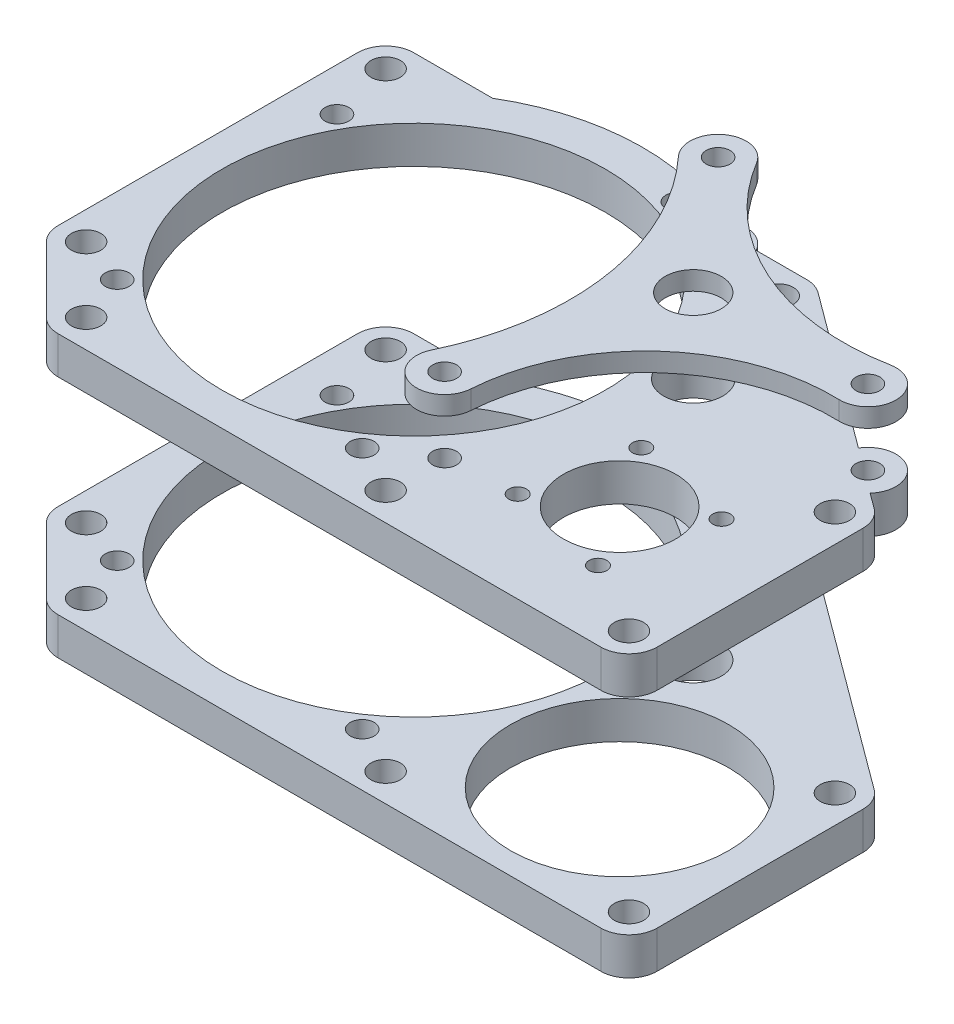
SolidWorks part; units mm, degrees
other "Outer Bottom Plate"
other "Outer Top Plate"
other "Stage 2 Retaining Plate"
material "Alum Plate"
ref_plane "Front Plane" through (0, 0, 0) normal (0, 0, 1) x (1, 0, 0)
ref_plane "Top Plane" through (0, 0, 0) normal (0, 1, 0) x (1, 0, 0)
ref_plane "Right Plane" through (0, 0, 0) normal (1, 0, 0) x (0, 0, -1)
other "Bounding Box"
ref_plane "Default Plane" through (-8.9266, -12.7485, 0) normal (-0.1736, 0.9848, 0) x (0.9848, 0.1736, 0)
sketch "Sketch1" plane through (0, 0, 0) normal (0, 1, 0) x (1, 0, 0)
  line L0 (-38.1, 76.2) -> (-38.1, -38.1)
  line L1 (-38.1, -38.1) -> (76.2, -38.1)
  line L2 (-38.1, 0) -> (0, 0) construction
  line L3 (0, 0) -> (0, -38.1) construction
  line L4 (-29.9699, -25.5926) -> (-25.5926, -29.9699) construction
  line L5 (-38.1, -38.1) -> (-27.7812, -27.7812) construction
  line L6 (-33.3375, -22.225) -> (-33.3375, 0) construction
  line L7 (-33.3375, 0) -> (-33.3375, 28.575) construction
  line L8 (-22.225, -33.3375) -> (0, -33.3375) construction
  line L9 (0, -33.3375) -> (28.575, -33.3375) construction
  line L10 (28.575, -33.3375) -> (69.85, -33.3375) construction
  circle A0 centre (0, 0) radius 32.5
  circle A1 centre (0, 0) radius 25
  circle A3 centre (50.8, -15.875) radius 17.5006
  circle A4 centre (0, 0) radius 31.115
  circle A5 centre (50.8, -15.875) radius 6.35
  circle A6 centre (38.3007, 9.1132) radius 8.255
  circle A7 centre (38.3007, 9.1132) radius 21.59
  circle A8 centre (-22.225, -33.3375) radius 4.7625
  circle A9 centre (-33.3375, 28.575) radius 4.7625
  circle A10 centre (69.85, -33.3375) radius 4.7625
  circle A11 centre (-33.3375, -22.225) radius 4.7625
  circle A12 centre (28.575, -33.3375) radius 4.7625
  point P24 (32.5, 0)
  point P26 (-32.5, 0)
  point P27 (33.2994, -15.875)
  point P38 (68.3006, -15.875)
  dimension "D1" = 65
  dimension "D2" = 50
  dimension "D3" = 35.0012
  dimension "D4" = 62.23
  dimension "D5" = 12.7
  dimension "D6" = 16.51
  dimension "D8" = 9.525
  dimension "D9" = 43.18
  dimension "D7" = 38.1
  dimension "D10" = 114.3
  dimension "D11" = 88.9
  dimension "D12" = 15.875
  dimension "D13" = 22.225
  dimension "D14" = 107.95
  dimension "D15" = 66.675
sketch "Sketch2" plane through (0, 0, 0) normal (0, 0, 1) x (1, 0, 0)
  line L0 (0, 0) -> (0, 19.05) construction
  line L1 (0, 19.05) -> (0, 24.1) construction
  line L2 (-32.5, 31.1) -> (32.5, 31.1)
  line L3 (-32.5, 31.1) -> (-32.5, 24.1)
  line L4 (-32.5, 24.1) -> (32.5, 24.1)
  line L5 (32.5, 31.1) -> (32.5, 24.1)
  line L6 (-32.5, 31.1) -> (32.5, 24.1) construction
  line L7 (-32.5, 24.1) -> (32.5, 31.1) construction
  line L8 (-32.5, 73.025) -> (32.5, 73.025)
  line L9 (-32.5, 73.025) -> (-32.5, 66.025)
  line L10 (-32.5, 66.025) -> (32.5, 66.025)
  line L11 (32.5, 73.025) -> (32.5, 66.025)
  line L12 (-32.5, 73.025) -> (32.5, 66.025) construction
  line L13 (-32.5, 66.025) -> (32.5, 73.025) construction
  line L14 (0, 31.1) -> (0, 66.025) construction
  line L15 (33.2994, 31.4297) -> (38.989, 21.575)
  line L16 (-38.1, 24.75) -> (83.6339, 24.75)
  line L17 (-38.1, 24.75) -> (-38.1, 31.1)
  line L18 (-38.1, 31.1) -> (83.6339, 31.1)
  line L19 (83.6339, 24.75) -> (83.6339, 31.1)
  line L20 (-38.1, 72.375) -> (83.6339, 72.375)
  line L21 (-38.1, 72.375) -> (-38.1, 66.025)
  line L22 (-38.1, 66.025) -> (83.6339, 66.025)
  line L23 (83.6339, 72.375) -> (83.6339, 66.025)
  line L24 (38.989, 21.575) -> (62.611, 21.575)
  line L25 (33.2994, 31.4297) -> (33.2994, 66.025)
  line L26 (33.2994, 66.025) -> (68.3006, 66.025)
  line L27 (68.3006, 31.4297) -> (68.3006, 66.025)
  line L28 (36.5821, 25.7439) -> (68.3006, 66.025) construction
  line L29 (33.2994, 66.025) -> (65.0179, 25.7439) construction
  line L30 (68.3006, 31.4297) -> (62.611, 21.575)
  line L31 (33.2994, 21.575) -> (33.2994, 31.4297) construction
  line L32 (33.2994, 21.575) -> (36.5821, 25.7439) construction
  line L33 (33.2994, 21.575) -> (38.989, 21.575) construction
  line L34 (62.611, 21.575) -> (68.3006, 21.575) construction
  line L35 (65.0179, 25.7439) -> (68.3006, 21.575) construction
  line L36 (68.3006, 21.575) -> (68.3006, 31.4297) construction
  line L37 (50.8, 21.575) -> (50.8, 66.025) construction
  line L38 (0, 0) -> (-69.131, 0) construction
  line L39 (-61.9887, 88.9) -> (127.3908, 88.9) construction
  line L41 (0, 85.075) -> (50.8, 85.075)
  line L42 (0, 85.075) -> (0, 81.9)
  line L43 (0, 81.9) -> (50.8, 81.9)
  line L44 (50.8, 85.075) -> (50.8, 81.9)
  line L45 (0, 85.075) -> (50.8, 81.9) construction
  line L46 (0, 81.9) -> (50.8, 85.075) construction
  circle A0 centre (0, 19.05) radius 19.05
  point P3 (0, 27.6)
  point P9 (0, 69.525)
  point P32 (50.8, 43.8)
  point P43 (25.4, 83.4875)
  dimension "D1" = 38.1
  dimension "D2" = 7
  dimension "D3" = 34.925
  dimension "D4" = 73.025
  dimension "D5" = 88.9
  dimension "D6" = 6.35
  dimension "D7" = 30
  dimension "D8" = 44.45
  dimension "D9" = 23.622
  dimension "D10" = 9.525
  dimension "D11" = 3.175
ref_plane "Plane1" through (0, 31.1, 0) normal (0, 1, 0) x (1, 0, 0)
sketch "Sketch3" plane through (0, 31.1, 0) normal (0, 1, 0) x (1, 0, 0)
  line L0 (-38.1, 76.2) -> (-38.1, -38.1) construction
  line L1 (-38.1, -38.1) -> (76.2, -38.1) construction
  line L2 (-38.1, 28.575) -> (-38.1, -22.225)
  line L3 (-22.225, -38.1) -> (69.85, -38.1)
  line L4 (-36.7051, -25.5926) -> (-25.5926, -36.7051)
  line L5 (-33.3375, 28.575) -> (33.3375, 28.575) construction
  line L6 (69.85, -33.3375) -> (69.85, 1.5875) construction
  line L7 (0, 0) -> (0, 28.575) construction
  line L8 (50.8, -15.875) -> (69.85, -15.875) construction
  line L9 (-33.3375, 33.3375) -> (-19.9483, 33.3375)
  line L10 (36.1683, 32.4049) -> (72.6808, 5.4174)
  line L11 (74.6125, 1.5875) -> (74.6125, -33.3375)
  line L12 (19.9483, 33.3375) -> (33.3375, 33.3375)
  circle A0 centre (0, 0) radius 32.5 construction
  circle A1 centre (0, 0) radius 32.5
  circle A2 centre (-33.3375, -22.225) radius 4.7625 construction
  circle A3 centre (-22.225, -33.3375) radius 4.7625 construction
  arc A4 (-38.1, -22.225) -> (-36.7051, -25.5926) centre (-33.3375, -22.225) ccw
  arc A5 (-25.5926, -36.7051) -> (-22.225, -38.1) centre (-22.225, -33.3375) ccw
  circle A6 centre (-33.3375, 28.575) radius 2.4892
  circle A7 centre (-33.3375, -22.225) radius 2.4892
  circle A8 centre (-22.225, -33.3375) radius 2.4892
  circle A9 centre (28.575, -33.3375) radius 2.4892
  circle A10 centre (50.8, -15.875) radius 18.5166
  circle A11 centre (38.3007, 9.1132) radius 4.7625
  circle A12 centre (50.8, -15.875) radius 17.5006 construction
  circle A13 centre (69.85, -33.3375) radius 2.4892
  circle A14 centre (69.85, 1.5875) radius 2.4892
  circle A15 centre (33.3375, 28.575) radius 2.4892
  arc A16 (33.3375, 33.3375) -> (36.1683, 32.4049) centre (33.3375, 28.575) cw
  arc A17 (74.6125, 1.5875) -> (72.6808, 5.4174) centre (69.85, 1.5875) ccw
  arc A18 (-38.1, 28.575) -> (-33.3375, 33.3375) centre (-33.3375, 28.575) cw
  circle A19 centre (-33.3375, 28.575) radius 4.7625 construction
  arc A20 (69.85, -38.1) -> (74.6125, -33.3375) centre (69.85, -33.3375) ccw
  circle A21 centre (69.85, -33.3375) radius 4.7625 construction
  arc A22 (-19.9483, 33.3375) -> (19.9483, 33.3375) centre (0, 0) cw
  dimension "D1" = 4.9784
  dimension "D2" = 1.016
  dimension "D3" = 9.525
  dimension "D4" = 6.35
extrude "Boss-Extrude1" add sketch "Sketch3" against normal up to vertex (6.35 mm away) up to point (-38.1, 24.75, 0)
ref_plane "Plane2" through (0, 66.025, 0) normal (0, 1, 0) x (1, 0, 0)
sketch "Sketch4" plane through (0, 66.025, 0) normal (0, 1, 0) x (1, 0, 0)
  line L0 (24.7301, 25.9051) -> (23.5327, 27.3867) construction
  line L1 (61.7669, 10.2769) -> (59.8642, 10.1825) construction
  line L2 (62.4497, 12.9795) -> (36.1683, 32.4049)
  line L7 (-36.7051, -25.5926) -> (-25.5926, -36.7051)
  line L8 (-22.225, -38.1) -> (69.85, -38.1)
  line L9 (74.6125, -33.3375) -> (74.6125, 1.5875)
  line L10 (72.6808, 5.4174) -> (36.1683, 32.4049)
  line L11 (33.3375, 33.3375) -> (19.9483, 33.3375)
  line L12 (-19.9483, 33.3375) -> (-33.3375, 33.3375)
  line L13 (-38.1, 28.575) -> (-38.1, -22.225)
  line L14 (-36.7051, -25.5926) -> (-25.5926, -36.7051)
  line L15 (-22.225, -38.1) -> (69.85, -38.1)
  line L16 (74.6125, -33.3375) -> (74.6125, 1.5875)
  line L17 (72.6808, 5.4174) -> (70.077, 7.3419)
  line L18 (33.3375, 33.3375) -> (24.7384, 33.3375)
  line L19 (-19.9483, 33.3375) -> (-33.3375, 33.3375)
  line L20 (-38.1, 28.575) -> (-38.1, -22.225)
  circle A0 centre (33.3375, 28.575) radius 2.4892 construction
  circle A1 centre (69.85, 1.5875) radius 2.4892 construction
  circle A2 centre (69.85, -33.3375) radius 2.4892 construction
  circle A3 centre (28.575, -33.3375) radius 2.4892 construction
  circle A4 centre (-22.225, -33.3375) radius 2.4892 construction
  circle A5 centre (-33.3375, -22.225) radius 2.4892 construction
  circle A6 centre (-33.3375, 28.575) radius 2.4892 construction
  arc A7 (-38.1, -22.225) -> (-36.7051, -25.5926) centre (-33.3375, -22.225) ccw
  arc A8 (-25.5926, -36.7051) -> (-22.225, -38.1) centre (-22.225, -33.3375) ccw
  arc A9 (69.85, -38.1) -> (74.6125, -33.3375) centre (69.85, -33.3375) ccw
  arc A10 (74.6125, 1.5875) -> (72.6808, 5.4174) centre (69.85, 1.5875) ccw
  arc A11 (36.1683, 32.4049) -> (33.3375, 33.3375) centre (33.3375, 28.575) ccw
  arc A12 (19.9483, 33.3375) -> (-19.9483, 33.3375) centre (0, 0) ccw
  arc A13 (-33.3375, 33.3375) -> (-38.1, 28.575) centre (-33.3375, 28.575) ccw
  arc A14 (-38.1, -22.225) -> (-36.7051, -25.5926) centre (-33.3375, -22.225) ccw
  arc A15 (-25.5926, -36.7051) -> (-22.225, -38.1) centre (-22.225, -33.3375) ccw
  arc A16 (69.85, -38.1) -> (74.6125, -33.3375) centre (69.85, -33.3375) ccw
  arc A17 (74.6125, 1.5875) -> (72.6808, 5.4174) centre (69.85, 1.5875) ccw
  arc A18 (36.1683, 32.4049) -> (33.3375, 33.3375) centre (33.3375, 28.575) ccw
  arc A19 (17.4463, 34.7124) -> (-19.9483, 33.3375) centre (0, 0) ccw
  arc A20 (-33.3375, 33.3375) -> (-38.1, 28.575) centre (-33.3375, 28.575) ccw
  circle A21 centre (33.3375, 28.575) radius 2.4892
  circle A22 centre (69.85, 1.5875) radius 2.4892
  circle A23 centre (69.85, -33.3375) radius 2.4892
  circle A24 centre (28.575, -33.3375) radius 2.4892
  circle A25 centre (-22.225, -33.3375) radius 2.4892
  circle A26 centre (-33.3375, -22.225) radius 2.4892
  circle A27 centre (-33.3375, 28.575) radius 2.4892
  circle A28 centre (38.3007, 9.1132) radius 5.0165
  circle A29 centre (38.3007, 9.1132) radius 4.7625 construction
  circle A30 centre (50.8, -15.875) radius 9.525
  circle A31 centre (0, 0) radius 32.5 construction
  circle A32 centre (0, 0) radius 32.5
  circle A33 centre (20.5392, 31.0908) radius 2.0193
  arc A34 (24.7384, 33.3375) -> (17.4463, 34.7124) centre (20.5392, 31.0908) ccw
  circle A36 centre (66.5236, 10.5128) radius 2.0193
  arc A37 (70.077, 7.3419) -> (62.4497, 12.9795) centre (66.5236, 10.5128) ccw
  circle A38 centre (28.8389, -23.5968) radius 2.0193
  circle A39 centre (28.8389, -23.5968) radius 4.7625 construction
  circle A40 centre (50.8, -15.875) radius 18.5166 construction
  circle A41 centre (38.3007, 9.1132) radius 21.59 construction
  circle A42 centre (69.85, 1.5875) radius 4.7625 construction
  arc A43 (61.7669, 10.2769) -> (68.1868, 6.0501) centre (66.5236, 10.5128) ccw construction
  arc A44 (62.4497, 12.9795) -> (61.7669, 10.2769) centre (66.5236, 10.5128) ccw construction
  arc A45 (23.5327, 27.3867) -> (24.7384, 33.3375) centre (20.5392, 31.0908) ccw construction
  arc A46 (17.4463, 34.7124) -> (17.9141, 27.1171) centre (20.5392, 31.0908) ccw construction
  arc A47 (17.9141, 27.1171) -> (23.5327, 27.3867) centre (20.5392, 31.0908) ccw construction
  circle A48 centre (-33.3375, 28.575) radius 4.7625 construction
  arc A49 (68.1868, 6.0501) -> (70.077, 7.3419) centre (66.5236, 10.5128) ccw construction
  dimension "D2" = 0.254
  dimension "D3" = 19.05
  dimension "D5" = 4.0386
  dimension "D4" = 1.905
  dimension "D1" = 0
extrude "Boss-Extrude2" add sketch "Sketch4" along normal up to vertex (6.35 mm away) separate body up to point (-38.1, 72.375, 0)
ref_plane "Plane3" through (0, 81.9, 0) normal (0, 1, 0) x (1, 0, 0)
sketch "Sketch6" plane through (0, 81.9, 0) normal (0, 1, 0) x (1, 0, 0)
  circle A0 centre (38.3007, 9.1132) radius 4.7625 construction
  circle A1 centre (28.8389, -23.5968) radius 2.0193 construction
  circle A2 centre (66.5236, 10.5128) radius 2.0193 construction
  circle A3 centre (20.5392, 31.0908) radius 2.0193 construction
  circle A4 centre (38.3007, 9.1132) radius 4.7625
  circle A5 centre (28.8389, -23.5968) radius 2.0193
  circle A6 centre (66.5236, 10.5128) radius 2.0193
  circle A7 centre (20.5392, 31.0908) radius 2.0193
  arc A8 (24.6177, 33.5499) -> (17.0461, 27.8535) centre (20.5392, 31.0908) ccw
  arc A9 (65.6397, 15.1925) -> (66.3605, 5.7531) centre (66.5236, 10.5128) cw
  arc A10 (24.5426, -21.5418) -> (33.5913, -23.9075) centre (28.8389, -23.5968) ccw
  arc A11 (24.6177, 33.5499) -> (65.6397, 15.1925) centre (58.3332, 53.8786) ccw
  arc A12 (33.5913, -23.9075) -> (66.3605, 5.7531) centre (65.2737, -25.9783) cw
  arc A13 (24.5426, -21.5418) -> (17.0461, 27.8535) centre (-15.556, -2.3609) ccw
  circle A16 centre (28.575, -33.3375) radius 4.7625 construction
  arc A17 (24.7384, 33.3375) -> (17.4463, 34.7124) centre (20.5392, 31.0908) ccw construction
  arc A18 (70.077, 7.3419) -> (62.4497, 12.9795) centre (66.5236, 10.5128) ccw construction
  dimension "D1" = 39.37
  dimension "D2" = 31.75
  dimension "D3" = 44.45
extrude "Boss-Extrude3" add sketch "Sketch6" along normal up to vertex (3.175 mm away) separate body up to point (50.8, 85.075, 0)
sketch "Sketch8" plane through (0, 72.375, 0) normal (0, 1, 0) x (1, 0, 0)
  line L0 (40.3166, -22.683) -> (43.992, -5.3916) construction
  line L1 (40.3166, -22.683) -> (57.608, -26.3584) construction
  line L2 (43.992, -5.3916) -> (61.2834, -9.067) construction
  line L3 (57.608, -26.3584) -> (61.2834, -9.067) construction
  line L4 (40.3166, -22.683) -> (61.2834, -9.067) construction
  line L5 (43.992, -5.3916) -> (57.608, -26.3584) construction
  line L6 (50.8, -15.875) -> (52.6377, -7.2293) construction
  line L7 (50.8, -15.875) -> (50.8, -6.35) construction
  circle A0 centre (50.8, -15.875) radius 9.525 construction
  circle A1 centre (43.992, -5.3916) radius 1.5
  circle A2 centre (61.2834, -9.067) radius 1.5
  circle A3 centre (57.608, -26.3584) radius 1.5
  circle A4 centre (40.3166, -22.683) radius 1.5
  point P1 (50.8, -15.875)
  dimension "D2" = 3
  dimension "D1" = 25
  dimension "D3" = 12
extrude "Cut-Extrude1" cut sketch "Sketch8" against normal through all
sketch "Sketch9" plane through (0, 72.375, 0) normal (0, 1, 0) x (1, 0, 0)
  line L0 (-26.826, 15.488) -> (-28.1458, 16.25) construction
  line L1 (10.0431, 30.9093) -> (9.5721, 29.4599) construction
  line L2 (-21.9033, -21.9033) -> (-22.981, -22.981) construction
  line L3 (17.7671, -25.3741) -> (18.6412, -26.6224) construction
  line L4 (0, 0) -> (0, 32.5) construction
  line L5 (-33.3375, -22.225) -> (-25.1452, -25.1452) construction
  line L6 (-25.1452, -25.1452) -> (-22.225, -33.3375) construction
  circle A0 centre (-25.1452, -25.1452) radius 2.0193
  circle A1 centre (20.3968, -29.1296) radius 2.0193
  circle A2 centre (-30.7965, 17.7803) radius 2.0193
  circle A3 centre (10.9889, 33.8202) radius 2.0193
  circle A4 centre (-30.7965, 17.7803) radius 4.5847 construction
  circle A5 centre (10.9889, 33.8202) radius 4.5847 construction
  circle A6 centre (-25.1452, -25.1452) radius 4.5847 construction
  circle A7 centre (20.3968, -29.1296) radius 4.5847 construction
  circle A8 centre (0, 0) radius 32.5 construction
  dimension "D1" = 4.0386
  dimension "D2" = 9.1694
  dimension "D3" = 1.524
  dimension "D4" = 18
  dimension "D5" = 60
  dimension "D6" = 145
extrude "Cut-Extrude2" cut sketch "Sketch9" against normal through all and the other way through all
sketch "Sketch10" plane through (0, 72.375, 0) normal (0, 1, 0) x (1, 0, 0)
  arc A0 (8.5338, 37.9012) -> (12.4606, 38.3496) centre (10.9889, 33.8202) cw
  arc A1 (17.4463, 34.7124) -> (-19.9483, 33.3375) centre (0, 0) ccw construction
  arc A2 (12.4606, 38.3496) -> (18.9643, 35.5854) centre (0, 0) cw
  arc A3 (24.7384, 33.3375) -> (17.4463, 34.7124) centre (20.5392, 31.0908) ccw construction
  arc A4 (18.9643, 35.5854) -> (17.4463, 34.7124) centre (20.5392, 31.0908) ccw
  arc A5 (17.4463, 34.7124) -> (8.5338, 37.9012) centre (0, 0) ccw
extrude "Boss-Extrude4" add sketch "Sketch10" against normal up to surface (6.35 mm away) up to face at (-25.1452, 66.025, 27.1645)
sketch "Sketch11" plane through (0, 31.1, 0) normal (0, 1, 0) x (1, 0, 0)
  line L0 (33.3375, 33.3375) -> (19.9483, 33.3375) construction
  line L1 (22.6842, 33.3375) -> (19.9483, 33.3375)
  arc A0 (12.4606, 38.3496) -> (8.5338, 37.9012) centre (10.9889, 33.8202) ccw construction
  arc A1 (12.4606, 38.3496) -> (8.5338, 37.9012) centre (10.9889, 33.8202) ccw
  arc A2 (19.9483, 33.3375) -> (-19.9483, 33.3375) centre (0, 0) ccw construction
  arc A3 (19.9483, 33.3375) -> (8.5338, 37.9012) centre (0, 0) ccw
  arc A4 (12.4606, 38.3496) -> (22.6842, 33.3375) centre (0, 0) cw
extrude "Boss-Extrude5" add sketch "Sketch11" against normal up to surface (6.35 mm away) up to face at (-25.1452, 24.75, 27.1645)
other "Save Bodies1"
